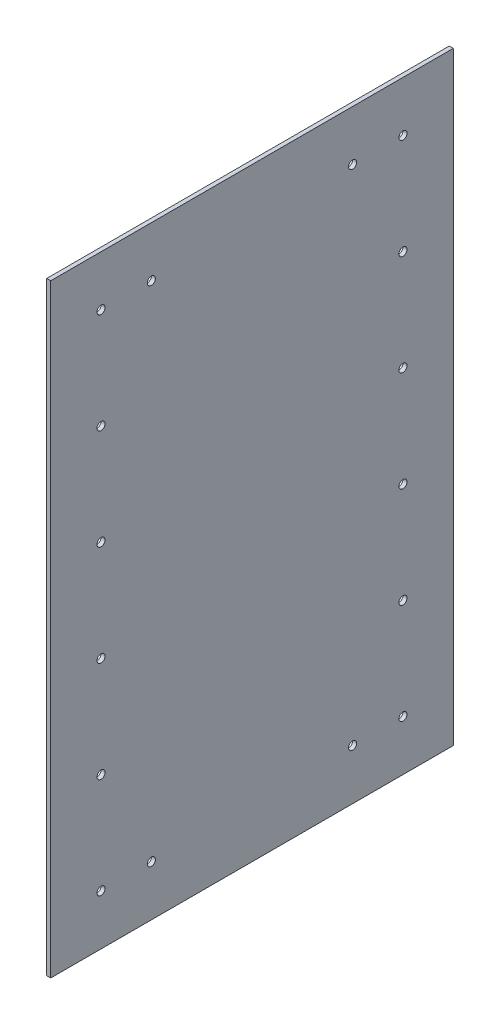
SolidWorks part; units mm, degrees
ref_plane "Спереди" through (0, 0, 0) normal (0, 0, 1) x (1, 0, 0)
ref_plane "Сверху" through (0, 0, 0) normal (0, 1, 0) x (1, 0, 0)
ref_plane "Справа" through (0, 0, 0) normal (1, 0, 0) x (0, 0, -1)
sketch "Эскиз1" plane through (0, 0, 0) normal (1, 0, 0) x (0, 0, -1)
  line L1 (-100, -150) -> (100, -150)
  line L2 (-100, -150) -> (-100, 150)
  line L3 (-100, 150) -> (100, 150)
  line L4 (100, -150) -> (100, 150)
  line L5 (-100, -150) -> (100, 150) construction
  line L6 (-100, 150) -> (100, -150) construction
  point P0 (0, 0)
  dimension "D1" = 200
  dimension "D2" = 300
extrude "Бобышка-Вытянуть1" add sketch "Эскиз1" along normal blind 2
sketch "Эскиз2" plane through (2, 0, 0) normal (1, 0, 0) x (0, 0, -1)
  line L0 (-100, 150) -> (-100, -150) construction
  line L1 (100, 150) -> (-100, 150) construction
  line L2 (-100, 0) -> (100, 0) construction
  line L3 (100, -150) -> (100, 150) construction
  line L4 (0, 150) -> (0, -150) construction
  line L5 (-100, -150) -> (100, -150) construction
  circle A0 centre (-75, 125) radius 2
  circle A1 centre (75, 125) radius 2
  circle A2 centre (75, -125) radius 2
  circle A3 centre (-75, -125) radius 2
  circle A4 centre (-75, 75) radius 2
  circle A5 centre (-75, 25) radius 2
  circle A6 centre (75, 25) radius 2
  circle A7 centre (75, 75) radius 2
  circle A8 centre (-75, -25) radius 2
  circle A9 centre (75, -25) radius 2
  circle A10 centre (75, -75) radius 2
  circle A11 centre (-75, -75) radius 2
  circle A12 centre (-50, 125) radius 2
  circle A13 centre (50, 125) radius 2
  circle A14 centre (50, -125) radius 2
  circle A15 centre (-50, -125) radius 2
  dimension "D1" = 150
  dimension "D2" = 4
  dimension "D5" = 50
  dimension "D7" = 50
  dimension "D9" = 4
  dimension "D3" = 25
  dimension "D4" = 25
  dimension "D6" = 50
  dimension "D8" = 100
extrude "Вырез-Вытянуть1" cut sketch "Эскиз2" against normal up to surface (2 mm away) up to face at (0, 0, 0)
